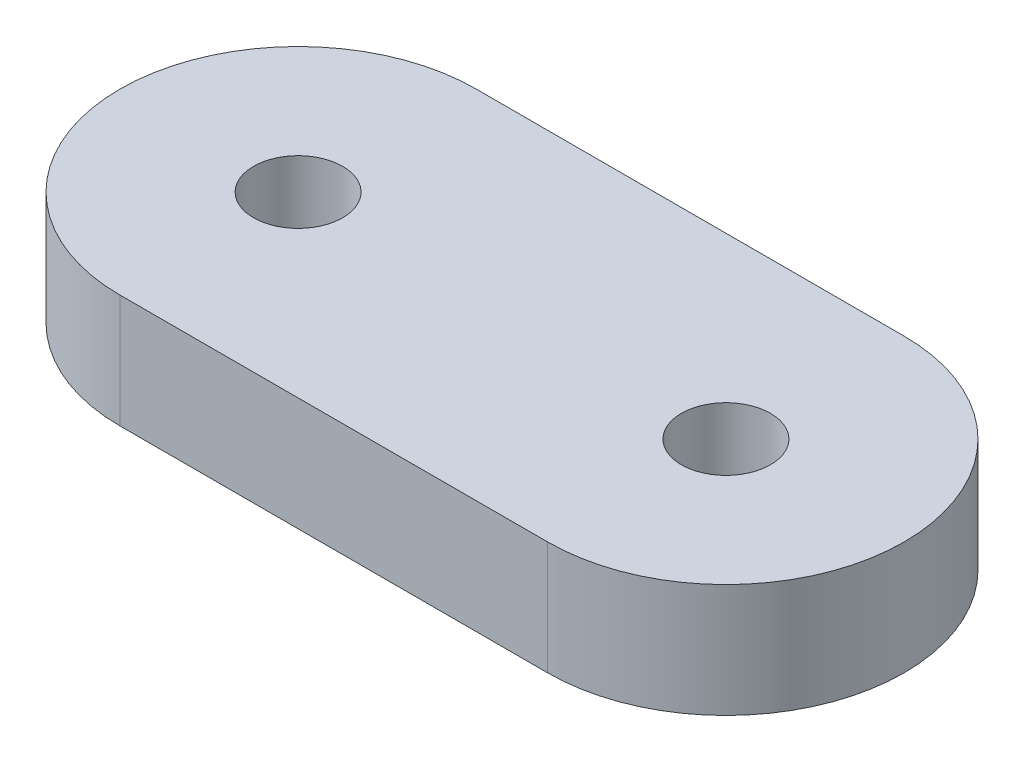
SolidWorks part; units mm, degrees
material "Beech"
ref_plane "Front Plane" through (0, 0, 0) normal (0, 0, 1) x (1, 0, 0)
ref_plane "Top Plane" through (0, 0, 0) normal (0, 1, 0) x (1, 0, 0)
ref_plane "Right Plane" through (0, 0, 0) normal (1, 0, 0) x (0, 0, -1)
sketch "Sketch1" plane through (0, 0, 0) normal (0, 1, 0) x (1, 0, 0)
  line L0 (0, 0) -> (12, 0) construction
  line L1 (0, 5) -> (12, 5)
  line L2 (0, -5) -> (12, -5)
  arc A0 (0, 5) -> (0, -5) centre (0, 0) ccw
  arc A1 (12, -5) -> (12, 5) centre (12, 0) ccw
  circle A2 centre (0, 0) radius 1.25
  circle A3 centre (12, 0) radius 1.25
  point P2 (6, 0)
  point P11 (0, 0)
  dimension "D3" = 2.5
  dimension "D4" = 2.5
  dimension "D1" = 12
  dimension "D2" = 5
extrude "Boss-Extrude1" add sketch "Sketch1" along normal blind 3.18
